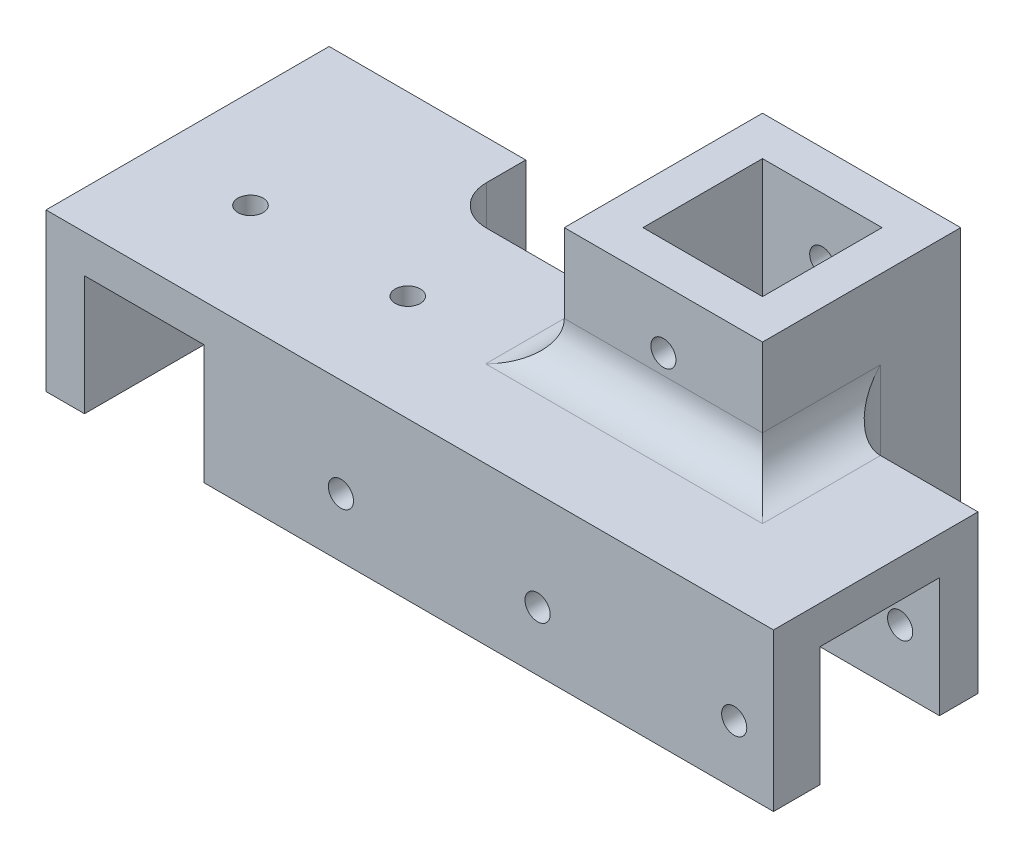
SolidWorks part; units mm, degrees
material "自定义塑料"
ref_plane "前视基准面" through (0, 0, 0) normal (0, 0, 1) x (1, 0, 0)
ref_plane "上视基准面" through (0, 0, 0) normal (0, 1, 0) x (1, 0, 0)
ref_plane "右视基准面" through (0, 0, 0) normal (1, 0, 0) x (0, 0, -1)
sketch "草图1" plane through (0, 0, 0) normal (0, 1, 0) x (1, 0, 0)
  line L0 (-50, 0) -> (30, 0) construction
  line L1 (-50, 7.5) -> (30, 7.5) construction
  line L2 (-50, -7.5) -> (30, -7.5) construction
  line L3 (-37.5, 12.5) -> (-12.6, 12.5)
  line L4 (-7.6, 22.7) -> (7.6, 22.7)
  line L5 (-7.6, 22.7) -> (-7.6, 7.5)
  line L6 (-7.6, 7.5) -> (7.6, 7.5)
  line L7 (7.6, 22.7) -> (7.6, 7.5)
  line L8 (-7.6, 22.7) -> (7.6, 7.5) construction
  line L9 (-7.6, 7.5) -> (7.6, 22.7) construction
  line L10 (-42.5, -27.5) -> (-42.5, 22.5) construction
  line L11 (-30, 0) -> (30, 0) construction
  line L12 (30, 12.5) -> (30, -13.5)
  line L13 (-50, -13.5) -> (-50, 22.5) construction
  line L14 (-12.6, 27.7) -> (-12.6, 12.5)
  line L15 (-12.6, 27.7) -> (12.6, 27.7)
  line L16 (12.6, 27.7) -> (12.6, 12.5)
  line L17 (12.6, 27.7) -> (12.6, 7.5) construction
  line L18 (12.6, 12.5) -> (30, 12.5)
  line L19 (-30, 12.5) -> (30, 12.5) construction
  line L20 (-12.6, 27.7) -> (-12.6, 7.5) construction
  line L21 (-30, 7.5) -> (30, 7.5) construction
  line L22 (-30, -7.5) -> (30, -7.5) construction
  line L23 (-50, -27.5) -> (-50, 22.5) construction
  line L24 (-57.5, -13.5) -> (-57.5, 22.5) construction
  line L25 (-42.5, -13.5) -> (-42.5, 22.5) construction
  line L26 (-37.5, 12.5) -> (-37.5, 22.5)
  line L27 (-37.5, 22.5) -> (-62.5, 22.5)
  line L28 (-62.5, 22.5) -> (-62.5, -13.5)
  line L30 (-57.5, -27.5) -> (-57.5, 22.5) construction
  line L31 (-62.5, -13.5) -> (30, -13.5)
  point P9 (0, 15.1)
  dimension "D3" = 15.2
  dimension "D4" = 30
  dimension "D8" = 50
  dimension "D6" = 6
  dimension "D11" = 15
  dimension "D12" = 5
  dimension "D1" = 7.5
  dimension "D2" = 7.5
  dimension "D5" = 5
  dimension "D7" = 5
  dimension "D9" = 7.5
  dimension "D10" = 7.5
extrude "凸台-拉伸1" add sketch "草图1" along normal blind 20
sketch "草图2" plane through (0, 20, 0) normal (0, 1, 0) x (1, 0, 0)
  line L0 (7.6, 7.5) -> (7.6, 22.7) construction
  line L1 (7.6, 7.5) -> (7.6, 22.7)
  line L2 (-7.6, 7.5) -> (7.6, 7.5) construction
  line L3 (-7.6, 22.7) -> (-7.6, 7.5) construction
  line L4 (7.6, 22.7) -> (-7.6, 22.7) construction
  line L5 (-7.6, 7.5) -> (7.6, 7.5)
  line L6 (-7.6, 22.7) -> (-7.6, 7.5)
  line L7 (7.6, 22.7) -> (-7.6, 22.7)
  line L8 (-12.6, 27.7) -> (-12.6, 2.5)
  line L9 (-12.6, 2.5) -> (12.6, 2.5)
  line L10 (12.6, 2.5) -> (12.6, 27.7)
  line L11 (12.6, 27.7) -> (-12.6, 27.7)
  dimension "D1" = 5
extrude "凸台-拉伸2" add sketch "草图2" along normal blind 15
sketch "草图3" plane through (30, 0, 0) normal (1, 0, 0) x (0, 0, -1)
  line L1 (-7.6, 15.2) -> (7.6, 15.2)
  line L2 (-7.6, 15.2) -> (-7.6, 0)
  line L3 (-7.6, 0) -> (7.6, 0)
  line L4 (7.6, 15.2) -> (7.6, 0)
  line L6 (-13.5, 0) -> (12.5, 0) construction
  point P4 (0, 15.2)
  dimension "D1" = 15.2
extrude "切除-拉伸1" cut sketch "草图3" against normal blind 80
sketch "草图4" plane through (0, 0, 13.5) normal (0, 0, 1) x (1, 0, 0)
  line L0 (-30, 7.5) -> (30, 7.5) construction
  line L1 (-62.5, 0) -> (30, 0) construction
  line L3 (0, 0) -> (0, 7.5) construction
  line L4 (0, 7.5) -> (0, 27.5) construction
  line L5 (-12.6, 35) -> (12.6, 35) construction
  circle A0 centre (0, 7.5) radius 1.6
  circle A1 centre (25, 7.5) radius 1.6
  circle A2 centre (-25, 7.5) radius 1.6
  circle A3 centre (0, 27.5) radius 1.6
  dimension "D1" = 3.2
  dimension "D2" = 50
  dimension "D3" = 3.2
  dimension "D4" = 7.5
  dimension "D5" = 7.5
extrude "切除-拉伸2" cut sketch "草图4" against normal through all
fillet "圆角1" radius 5 6 edges at (12.6, 10, -12.5) (-12.6, 10, -12.5) (-12.6, 20, -7.5) (0, 20, -2.5) (12.6, 20, -7.5) (-37.5, 10, -12.5)
sketch "草图5" plane through (0, 0, 13.5) normal (0, 0, 1) x (1, 0, 0)
  line L0 (-62.5, 0) -> (30, 0) construction
  line L1 (-57.6, 0) -> (-42.4, 0)
  line L2 (-57.6, 0) -> (-57.6, 15.2)
  line L3 (-57.6, 15.2) -> (-42.4, 15.2)
  line L4 (-42.4, 0) -> (-42.4, 15.2)
  point P6 (-50, 0)
  dimension "D1" = 50
  dimension "D2" = 15.2
extrude "切除-拉伸3" cut sketch "草图5" against normal through all
sketch "草图6" plane through (-62.5, 0, 0) normal (-1, 0, 0) x (0, 0, 1)
  line L0 (-22.5, 0) -> (13.5, 0) construction
  circle A0 centre (-15, 7.5) radius 1.6
  dimension "D1" = 7.5
  dimension "D2" = 15
  dimension "D3" = 3.2
extrude "切除-拉伸4" cut sketch "草图6" against normal up to surface (27.1382 mm away)
sketch "草图7" plane through (0, 20, 0) normal (0, 1, 0) x (1, 0, 0)
  line L0 (0, 0) -> (-50, 0) construction
  circle A0 centre (-50, 0) radius 1.6
  circle A1 centre (-30, 0) radius 1.6
  dimension "D2" = 30
  dimension "D3" = 3.2
  dimension "D1" = 50
extrude "切除-拉伸5" cut sketch "草图7" against normal up to next
